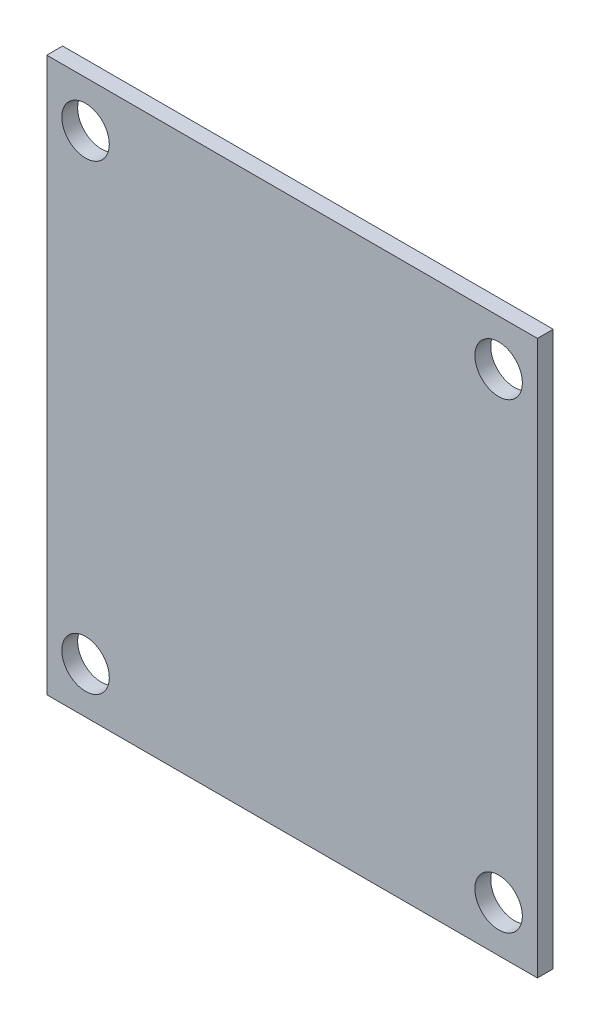
SolidWorks part; units mm, degrees
ref_plane "Front Plane" through (0, 0, 0) normal (0, 0, 1) x (1, 0, 0)
ref_plane "Top Plane" through (0, 0, 0) normal (0, 1, 0) x (1, 0, 0)
ref_plane "Right Plane" through (0, 0, 0) normal (1, 0, 0) x (0, 0, -1)
other "Graphic1"
other "Graphic (Closed) -1"
sketch "Sketch1" plane through (0, 0, 0) normal (0, 0, 1) x (1, 0, 0)
  line L0 (42.3701, 66.017) -> (44.8201, 66.017) construction
  line L1 (44.8201, 66.017) -> (44.8201, 63.107) construction
  line L2 (42.3701, 66.017) -> (70.9201, 66.017) construction
  line L3 (70.9201, 66.017) -> (70.9201, 63.107) construction
  line L4 (42.3701, 66.017) -> (42.3701, 33.927) construction
  line L5 (42.3701, 33.927) -> (44.8201, 33.927) construction
  line L6 (44.8201, 63.107) -> (70.9201, 63.107) construction
  line L7 (44.8201, 63.107) -> (44.8201, 33.927) construction
  line L8 (70.9201, 63.107) -> (70.9201, 33.927) construction
  line L9 (44.8201, 33.927) -> (70.9201, 33.927) construction
  line L11 (42.3701, 66.017) -> (73.3701, 66.017)
  line L12 (42.3701, 66.017) -> (42.3701, 31.017)
  line L13 (42.3701, 31.017) -> (73.3701, 31.017)
  line L14 (73.3701, 66.017) -> (73.3701, 31.017)
  circle A0 centre (44.8201, 63.107) radius 1.5
  circle A1 centre (70.9201, 63.107) radius 1.5
  circle A2 centre (44.8201, 33.927) radius 1.5
  circle A3 centre (70.9201, 33.927) radius 1.5
  point P2 (42.3701, 66.017)
  dimension "D1" = 3
  dimension "D2" = 2.45
  dimension "D3" = 2.91
  dimension "D4" = 28.55
  dimension "D6" = 32.09
extrude "Boss-Extrude1" add sketch "Sketch1" along normal blind 1
